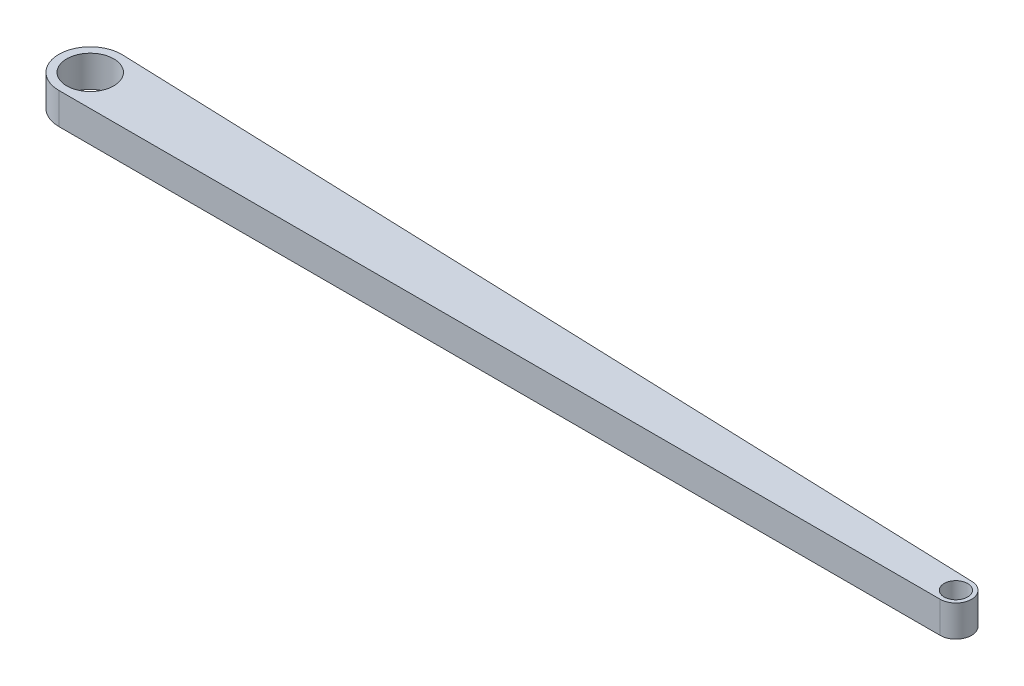
SolidWorks part; units mm, degrees
ref_plane "Front Plane" through (0, 0, 0) normal (0, 0, 1) x (1, 0, 0)
ref_plane "Top Plane" through (0, 0, 0) normal (0, 1, 0) x (1, 0, 0)
ref_plane "Right Plane" through (0, 0, 0) normal (1, 0, 0) x (0, 0, -1)
sketch "Sketch1" plane through (0, 0, 0) normal (0, 1, 0) x (1, 0, 0)
  line L0 (0, 0) -> (1800, 0)
  line L1 (0, 0) -> (0, 128)
  line L2 (1800, 0) -> (1800, 64)
  line L3 (0, 128) -> (1800, 64)
  circle A0 centre (0, 64) radius 64
  circle A1 centre (0, 64) radius 48
  circle A2 centre (1800, 32) radius 32
  circle A3 centre (1800, 32) radius 24
  dimension "D4" = 96
  dimension "D5" = 48
  dimension "D1" = 1800
  dimension "D2" = 128
  dimension "D3" = 64
extrude "Boss-Extrude1" add sketch "Sketch1" along normal blind 64 contours A2 L3 A0 L0 | A1 L1 A0 | A1 L1 A0 L3 | A3 L2 A2 | A3 L2 A2
